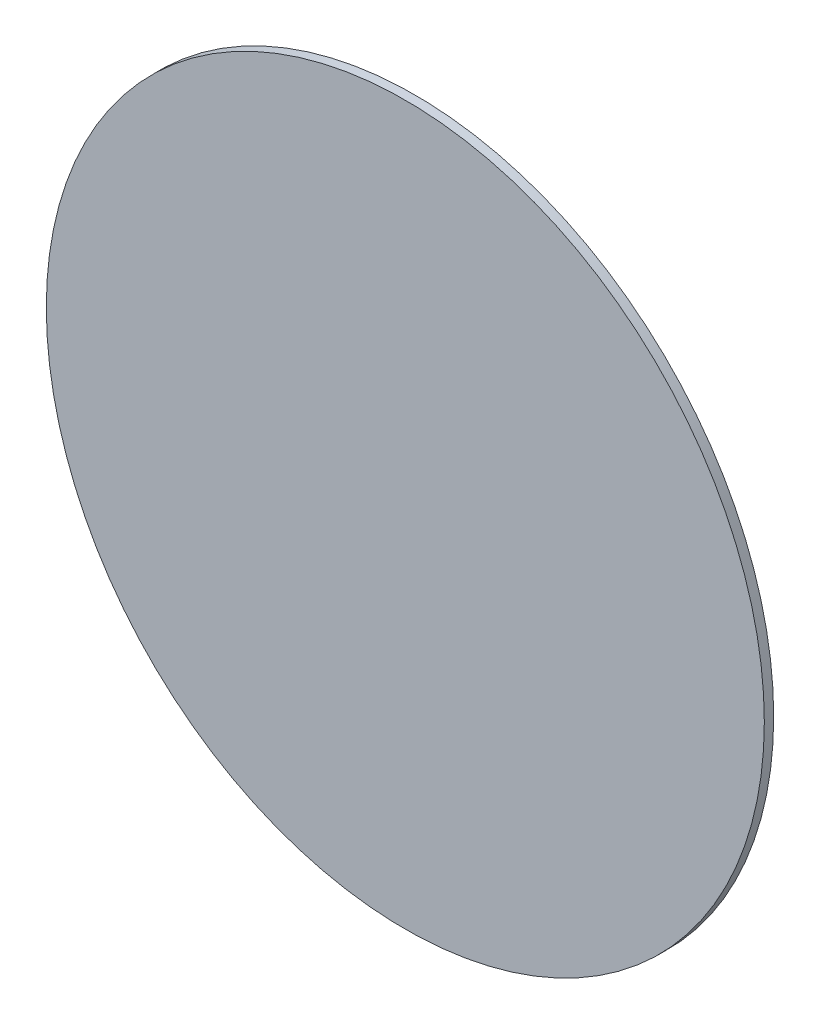
SolidWorks part; units mm, degrees
material "Plastique personnalisé"
ref_plane "Plan de face" through (0, 0, 0) normal (0, 0, 1) x (1, 0, 0)
ref_plane "Plan de dessus" through (0, 0, 0) normal (0, 1, 0) x (1, 0, 0)
ref_plane "Plan de droite" through (0, 0, 0) normal (1, 0, 0) x (0, 0, -1)
sketch "Esquisse1" plane through (0, 0, 0) normal (0, 0, 1) x (1, 0, 0)
  circle A0 centre (0, 0) radius 383.2
  dimension "D1" = 766.4
extrude "Boss.-Extru.1" add sketch "Esquisse1" along normal blind 10
